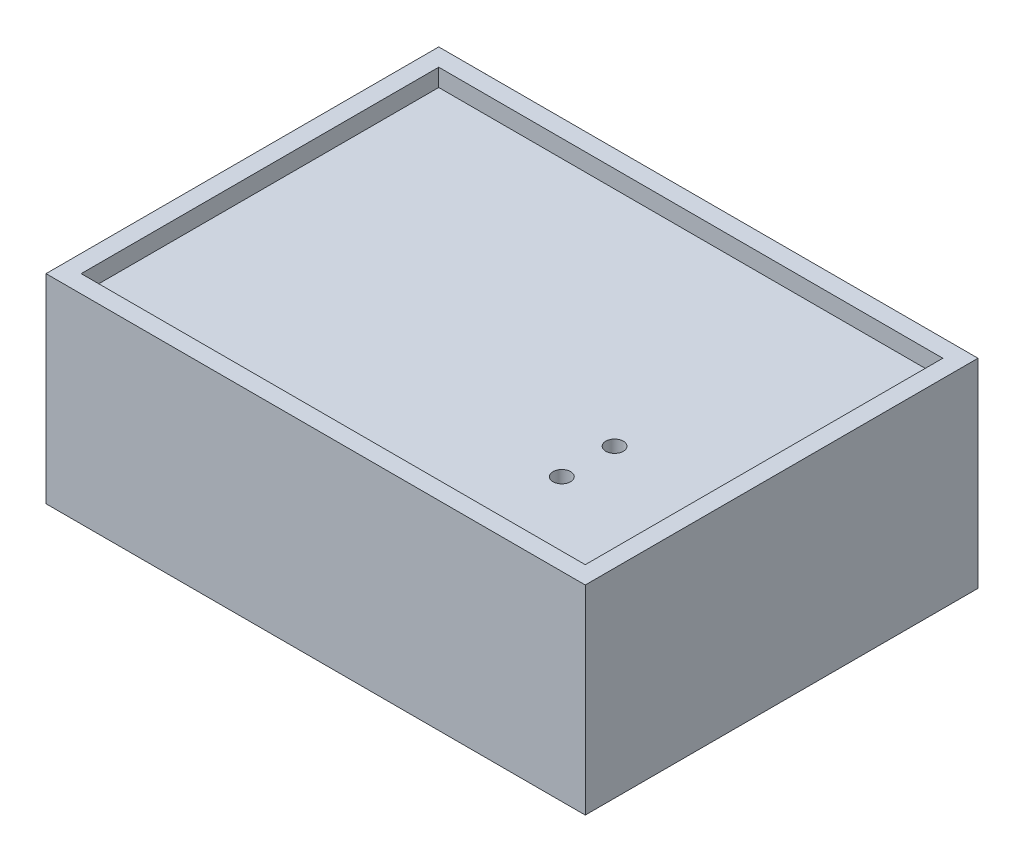
SolidWorks part; units mm, degrees
ref_plane "前视基准面" through (0, 0, 0) normal (0, 0, 1) x (1, 0, 0)
ref_plane "上视基准面" through (0, 0, 0) normal (0, 1, 0) x (1, 0, 0)
ref_plane "右视基准面" through (0, 0, 0) normal (1, 0, 0) x (0, 0, -1)
sketch "草图1" plane through (0, 0, 0) normal (0, 1, 0) x (1, 0, 0)
  line L1 (-46, -33.5) -> (46, -33.5)
  line L2 (-46, -33.5) -> (-46, 33.5)
  line L3 (-46, 33.5) -> (46, 33.5)
  line L4 (46, -33.5) -> (46, 33.5)
  line L5 (-46, -33.5) -> (46, 33.5) construction
  line L6 (-46, 33.5) -> (46, -33.5) construction
  point P0 (0, 0)
  dimension "D1" = 92
  dimension "D2" = 67
extrude "凸台-拉伸1" add sketch "草图1" along normal blind 34
sketch "草图2" plane through (0, 34, 0) normal (0, 1, 0) x (1, 0, 0)
  line L8 (43, -30.5) -> (43, 30.5)
  line L9 (43, 30.5) -> (-43, 30.5)
  line L10 (-43, 30.5) -> (-43, -30.5)
  line L11 (-43, -30.5) -> (43, -30.5)
  line L12 (43, -30.5) -> (43, 30.5)
  line L13 (43, 30.5) -> (-43, 30.5)
  line L14 (-43, 30.5) -> (-43, -30.5)
  line L15 (-43, -30.5) -> (43, -30.5)
  dimension "D1" = 3
extrude "切除-拉伸1" cut sketch "草图2" against normal blind 3
sketch "草图3" plane through (0, 31, 0) normal (0, 1, 0) x (1, 0, 0)
  line L0 (-43, -30.5) -> (43, -30.5) construction
  line L2 (43, -30.5) -> (43, 30.5) construction
  circle A0 centre (25, -16.5) radius 1.5
  circle A1 centre (25, -7.5) radius 1.5
  dimension "D4" = 3
  dimension "D1" = 9
  dimension "D2" = 14
  dimension "D3" = 18
extrude "切除-拉伸2" cut sketch "草图3" against normal blind 3
sketch "草图4" plane through (0, 0, 0) normal (0, -1, 0) x (1, 0, 0)
  line L8 (43, -30.5) -> (43, 30.5)
  line L9 (43, 30.5) -> (-43, 30.5)
  line L10 (-43, 30.5) -> (-43, -30.5)
  line L11 (-43, -30.5) -> (43, -30.5)
  line L12 (43, -30.5) -> (43, 30.5)
  line L13 (43, 30.5) -> (-43, 30.5)
  line L14 (-43, 30.5) -> (-43, -30.5)
  line L15 (-43, -30.5) -> (43, -30.5)
  dimension "D1" = 3
extrude "切除-拉伸3" cut sketch "草图4" against normal blind 3
sketch "草图5" plane through (0, 3, 0) normal (0, -1, 0) x (1, 0, 0)
  line L0 (0, 0) -> (-43, 0) construction
  line L1 (-43, 30.5) -> (-43, -30.5) construction
  line L2 (-10, 16.343) -> (-10, -10.4073) construction
  line L3 (-46, -33.5) -> (-46, 33.5) construction
  circle A0 centre (-39, 24.5) radius 1.5
  circle A1 centre (19, 24.5) radius 1.5
  circle A2 centre (19, -24.5) radius 1.5
  circle A3 centre (-39, -24.5) radius 1.5
  dimension "D4" = 3
  dimension "D1" = 58
  dimension "D2" = 49
  dimension "D3" = 7
extrude "切除-拉伸4" cut sketch "草图5" against normal blind 3
